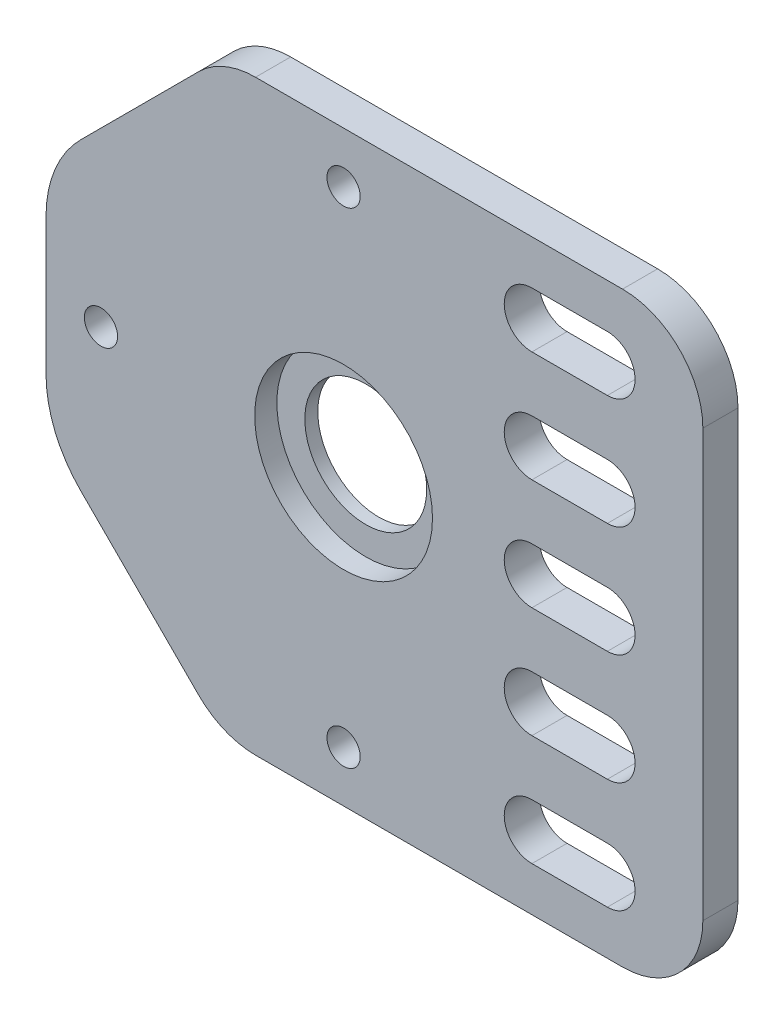
SolidWorks part; units mm, degrees
ref_plane "Plan de face" through (0, 0, 0) normal (0, 0, 1) x (1, 0, 0)
ref_plane "Plan de dessus" through (0, 0, 0) normal (0, 1, 0) x (1, 0, 0)
ref_plane "Plan de droite" through (0, 0, 0) normal (1, 0, 0) x (0, 0, -1)
sketch "Esquisse1" plane through (0, 0, 0) normal (0, 0, 1) x (1, 0, 0)
  line L0 (25.18, -26.5) -> (-7.947, -26.5)
  line L1 (-13.0735, -24.3765) -> (-23.7319, -13.7181)
  line L2 (-26.86, -6.1662) -> (-26.86, 6.1662)
  line L3 (-23.7319, 13.7181) -> (-13.0735, 24.3765)
  line L4 (-7.947, 26.5) -> (25.18, 26.5)
  line L5 (32.43, 19.25) -> (32.43, -19.25)
  line L6 (-26.86, 0) -> (0, 0) construction
  line L7 (0, 0) -> (32.43, 0) construction
  line L8 (-21.9, 0) -> (0, 21.9) construction
  line L9 (17, 0) -> (17, 20) construction
  line L10 (17, 20) -> (23.81, 20) construction
  line L11 (17, 22.5) -> (23.81, 22.5)
  line L12 (17, 17.5) -> (23.81, 17.5)
  line L13 (17, 10) -> (23.81, 10) construction
  line L14 (17, 12.5) -> (23.81, 12.5)
  line L15 (17, 7.5) -> (23.81, 7.5)
  line L16 (17, 0) -> (23.81, 0) construction
  line L17 (17, 2.5) -> (23.81, 2.5)
  line L18 (17, -2.5) -> (23.81, -2.5)
  line L19 (17, -10) -> (23.81, -10) construction
  line L20 (17, -7.5) -> (23.81, -7.5)
  line L21 (17, -12.5) -> (23.81, -12.5)
  line L22 (17, -20) -> (23.81, -20) construction
  line L23 (17, -17.5) -> (23.81, -17.5)
  line L24 (17, -22.5) -> (23.81, -22.5)
  line L25 (-21.9, 0) -> (0, -21.9) construction
  line L26 (0, -21.9) -> (-10.95, -10.95) construction
  line L27 (-10.95, -10.95) -> (-10.95, -26.5) construction
  circle A0 centre (0, 0) radius 5.5
  circle A1 centre (0, 21.9) radius 1.5
  circle A2 centre (-21.9, 0) radius 1.5
  circle A3 centre (0, -21.9) radius 1.5
  arc A4 (17, 22.5) -> (17, 17.5) centre (17, 20) ccw
  arc A5 (23.81, 17.5) -> (23.81, 22.5) centre (23.81, 20) ccw
  arc A6 (17, 12.5) -> (17, 7.5) centre (17, 10) ccw
  arc A7 (23.81, 7.5) -> (23.81, 12.5) centre (23.81, 10) ccw
  arc A8 (17, 2.5) -> (17, -2.5) centre (17, 0) ccw
  arc A9 (23.81, -2.5) -> (23.81, 2.5) centre (23.81, 0) ccw
  arc A10 (17, -7.5) -> (17, -12.5) centre (17, -10) ccw
  arc A11 (23.81, -12.5) -> (23.81, -7.5) centre (23.81, -10) ccw
  arc A12 (17, -17.5) -> (17, -22.5) centre (17, -20) ccw
  arc A13 (23.81, -22.5) -> (23.81, -17.5) centre (23.81, -20) ccw
  arc A14 (-23.7319, -13.7181) -> (-26.86, -6.1662) centre (-16.18, -6.1662) cw
  arc A15 (-26.86, 6.1662) -> (-23.7319, 13.7181) centre (-16.18, 6.1662) cw
  arc A16 (-7.947, -26.5) -> (-13.0735, -24.3765) centre (-7.947, -19.25) cw
  arc A17 (25.18, -26.5) -> (32.43, -19.25) centre (25.18, -19.25) ccw
  arc A18 (25.18, 26.5) -> (32.43, 19.25) centre (25.18, 19.25) cw
  arc A19 (-13.0735, 24.3765) -> (-7.947, 26.5) centre (-7.947, 19.25) cw
  point P15 (20.405, 20)
  point P27 (20.405, 10)
  point P34 (20.405, 0)
  point P41 (20.405, -10)
  point P48 (20.405, -20)
  point P63 (32.43, -26.5)
  point P66 (32.43, 26.5)
  dimension "D1" = 11
  dimension "D6" = 3
  dimension "D14" = 10.68
  dimension "D15" = 7.25
  dimension "D2" = 53
  dimension "D3" = 59.29
  dimension "D4" = 45
  dimension "D5" = 26.86
  dimension "D7" = 21.9
  dimension "D9" = 20
  dimension "D10" = 43.86
  dimension "D11" = 6.81
  dimension "D12" = 5
  dimension "D13" = 5
  dimension "D8" = 3
extrude "Boss.-Extru.1" add sketch "Esquisse1" along normal mid plane 3.17
sketch "Esquisse2" plane through (0, 0, 1.585) normal (0, 0, 1) x (1, 0, 0)
  circle A0 centre (0, 0) radius 8.025
  dimension "D1" = 16.05
extrude "Enlèv. mat.-Extru.1" cut sketch "Esquisse2" against normal blind 2
